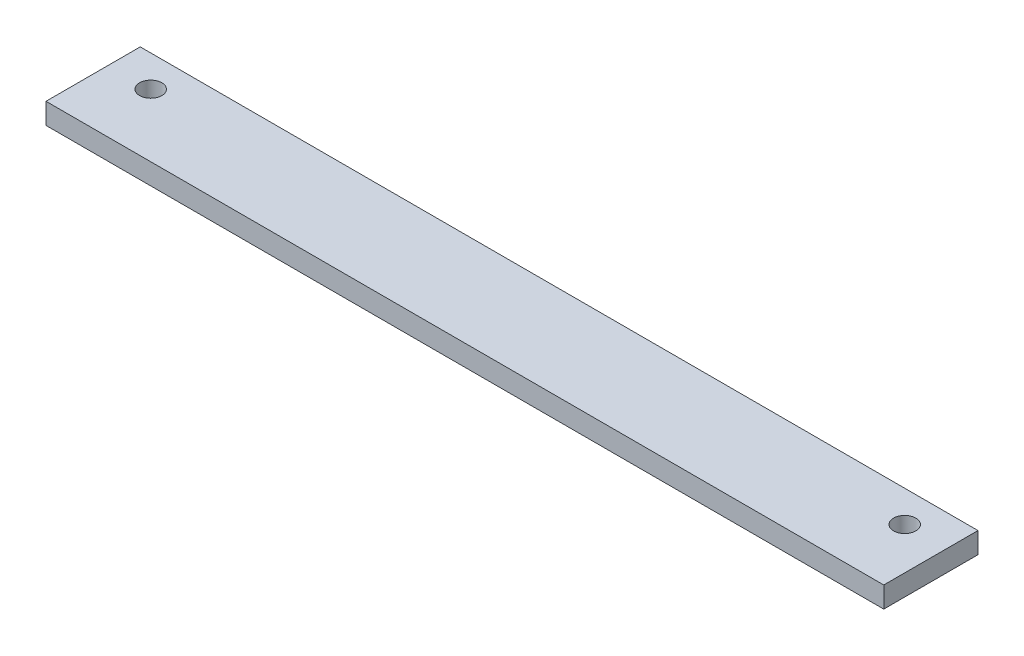
SolidWorks part; units mm, degrees
ref_plane "Front Plane" through (0, 0, 0) normal (0, 0, 1) x (1, 0, 0)
ref_plane "Top Plane" through (0, 0, 0) normal (0, 1, 0) x (1, 0, 0)
ref_plane "Right Plane" through (0, 0, 0) normal (1, 0, 0) x (0, 0, -1)
sketch "Sketch2" plane through (0, 0, 0) normal (0, 1, 0) x (1, 0, 0)
  line L1 (0, 0) -> (254, 0)
  line L2 (0, 0) -> (0, 28.575)
  line L3 (0, 28.575) -> (254, 28.575)
  line L4 (254, 0) -> (254, 28.575)
  dimension "D1" = 254
  dimension "D2" = 28.575
extrude "Boss-Extrude1" add sketch "Sketch2" along normal blind 6.35
hole_wizard "17/64 (0.26563) Diameter Hole1" positions "Sketch3" profile "Sketch4" hole size "17/64" standard "ANSI Inch" end condition through all
sketch "Sketch3" plane through (0, 6.35, 0) normal (0, 1, 0) x (1, 0, 0)
  line L0 (254, 28.575) -> (0, 28.575) construction
  line L1 (0, 28.575) -> (0, 0) construction
  line L2 (254, 0) -> (254, 28.575) construction
  point P0 (12.7, 19.05)
  point P2 (241.3, 19.05)
  dimension "D1" = 9.525
  dimension "D2" = 12.7
  dimension "D3" = 12.7
sketch "Sketch4" plane through (12.7, 6.35, -19.05) normal (1, 0, 0) x (0, 0, 1)
  line L0 (0, 0) -> (0, 6.35)
  line L1 (0, 6.35) -> (3.3735, 6.35)
  line L2 (3.3735, 6.35) -> (3.3735, 0)
  line L5 (3.3735, 0) -> (0, 0)
  line L11 (0, -6.35) -> (0, 107.95) construction
  dimension "Thru Hole Dia." = 6.747
  dimension "Thru Hole Depth" = 6.35
